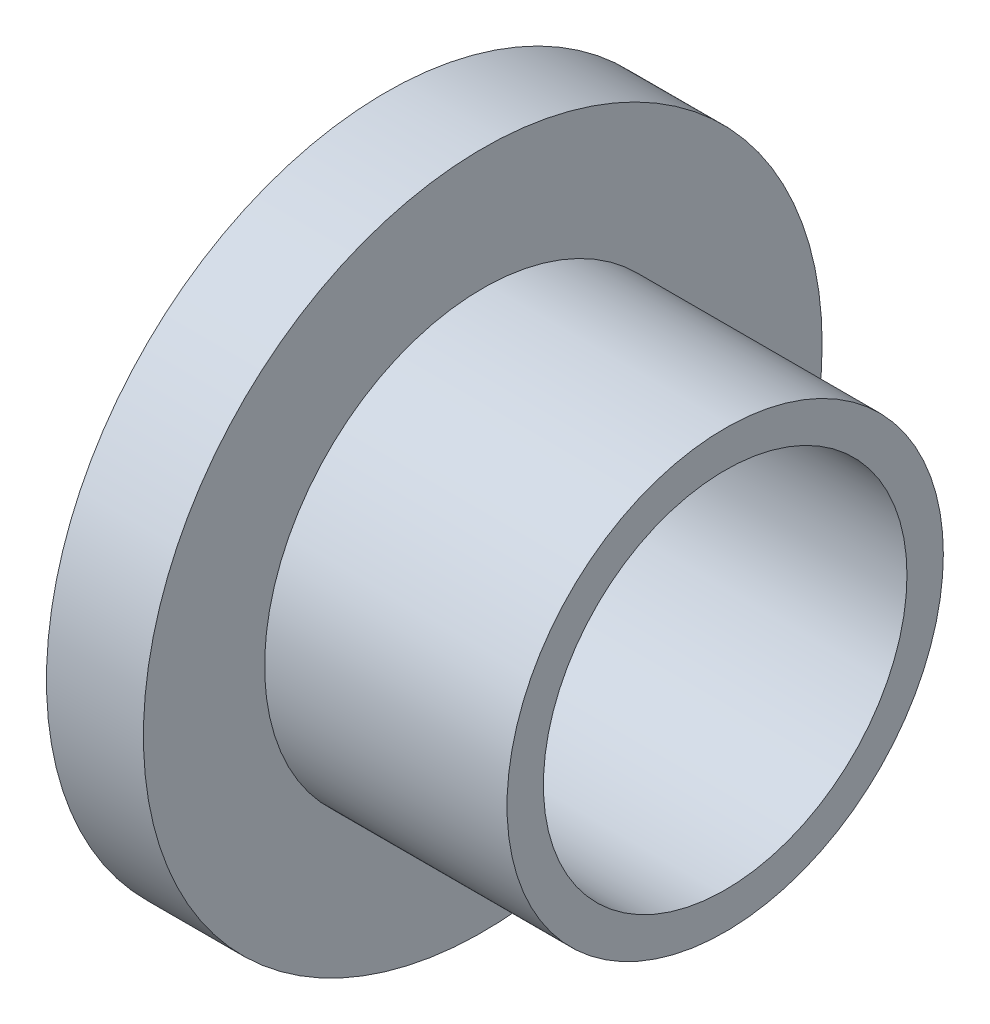
SolidWorks part; units mm, degrees
material "普通碳钢"
ref_plane "前视基准面" through (0, 0, 0) normal (0, 0, 1) x (1, 0, 0)
ref_plane "上视基准面" through (0, 0, 0) normal (0, 1, 0) x (1, 0, 0)
ref_plane "右视基准面" through (0, 0, 0) normal (1, 0, 0) x (0, 0, -1)
sketch "草图1" plane through (0, 0, 0) normal (1, 0, 0) x (0, 0, -1)
  circle A0 centre (0, 0) radius 70
  dimension "D1" = 140
extrude "凸台-拉伸1" add sketch "草图1" along normal blind 70
sketch "草图2" plane through (70, 0, 0) normal (1, 0, 0) x (0, 0, -1)
  circle A0 centre (0, 0) radius 37.5
  dimension "D1" = 75
extrude "切除-拉伸1" cut sketch "草图2" against normal through all
sketch "草图3" plane through (70, 0, 0) normal (1, 0, 0) x (0, 0, -1)
  circle A0 centre (0, 0) radius 45
  dimension "D1" = 90
extrude "切除-拉伸2" cut sketch "草图3" against normal offset from surface (50 mm away) 20 flip side to cut up to face at (0, 0, -37.5)
